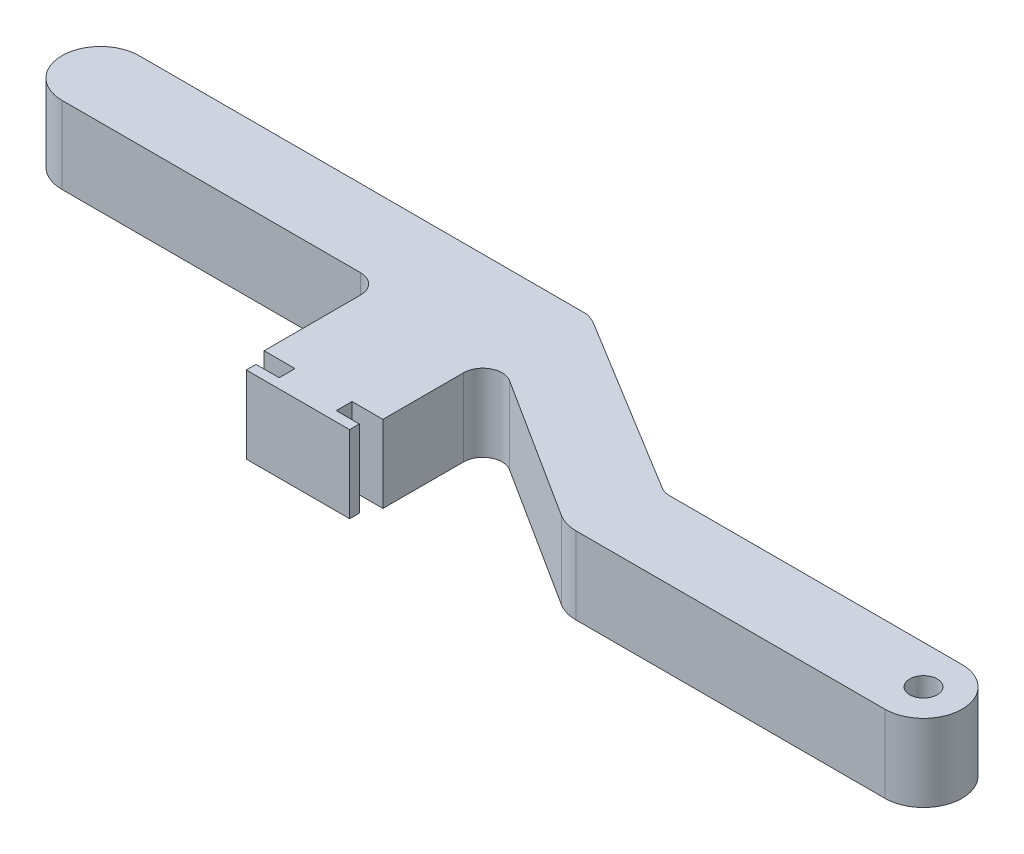
SolidWorks part; units mm, degrees
ref_plane "Front Plane" through (0, 0, 0) normal (0, 0, 1) x (1, 0, 0)
ref_plane "Top Plane" through (0, 0, 0) normal (0, 1, 0) x (1, 0, 0)
ref_plane "Right Plane" through (0, 0, 0) normal (1, 0, 0) x (0, 0, -1)
sketch "Sketch1" plane through (0, 0, 0) normal (0, 1, 0) x (1, 0, 0)
  line L0 (1.4303, -2.1555) -> (-22.6284, -2.1555)
  line L1 (-39.8537, -8.5055) -> (-42.3937, -8.5055)
  line L2 (-47.0837, -8.5055) -> (-49.6237, -8.5055)
  line L3 (-47.0837, -9.8055) -> (-48.9887, -9.8055)
  line L4 (-42.3937, -8.5055) -> (-42.3937, -9.8055)
  line L5 (-23.9697, -8.5055) -> (1.4303, -8.5055)
  line L6 (-47.0837, -8.5055) -> (-47.0837, -9.8055)
  line L7 (-40.4887, -9.8055) -> (-42.3937, -9.8055)
  line L8 (-40.4887, -9.8055) -> (-40.4887, -10.6055)
  line L9 (-40.4887, -10.6055) -> (-48.9887, -10.6055)
  line L10 (-48.9887, -9.8055) -> (-48.9887, -10.6055)
  line L11 (-25.6267, -8.0388) -> (-37.4136, -0.5341)
  line L12 (-23.4569, -1.9221) -> (-37.8811, 6.9028)
  line L14 (-51.2112, 1.0195) -> (-75.7786, 1.0195)
  line L15 (-38.9595, 7.3695) -> (-75.7786, 7.3695)
  line L17 (-39.8537, -1.8732) -> (-39.8537, -8.5055)
  line L19 (-49.6237, -0.568) -> (-49.6237, -8.5055)
  circle A0 centre (1.4303, -5.3305) radius 1.1303
  arc A1 (-51.2112, 1.0195) -> (-49.6237, -0.568) centre (-51.2112, -0.568) cw
  arc A2 (1.4303, -8.5055) -> (1.4303, -2.1555) centre (1.4303, -5.3305) ccw
  arc A3 (-25.6267, -8.0388) -> (-23.9697, -8.5055) centre (-23.9697, -5.3305) ccw
  arc A4 (-37.4136, -0.5341) -> (-39.8537, -1.8732) centre (-38.2662, -1.8732) ccw
  arc A5 (-23.4569, -1.9221) -> (-22.6284, -2.1555) centre (-22.6284, -0.568) ccw
  arc A6 (-75.7786, 7.3695) -> (-75.7786, 1.0195) centre (-75.7786, 4.1945) ccw
  arc A7 (-37.8811, 6.9028) -> (-38.9595, 7.3695) centre (-39.6595, 4.2726) ccw
  point P17 (-31.7539, -0.568)
  point P24 (-57.9476, 4.1945)
  dimension "D1" = 2.2606
  dimension "D2" = 1.5875
  dimension "D4" = 48.514
  dimension "D5" = 1.3
  dimension "D7" = 1.905
  dimension "D11" = 3.175
  dimension "D12" = 2.54
  dimension "D13" = 3.175
  dimension "D3" = 4.69
  dimension "D6" = 1.905
  dimension "D8" = 0.8
  dimension "D9" = 25.4
  dimension "D10" = 2.54
extrude "Boss-Extrude1" add sketch "Sketch1" along normal blind 6.35
